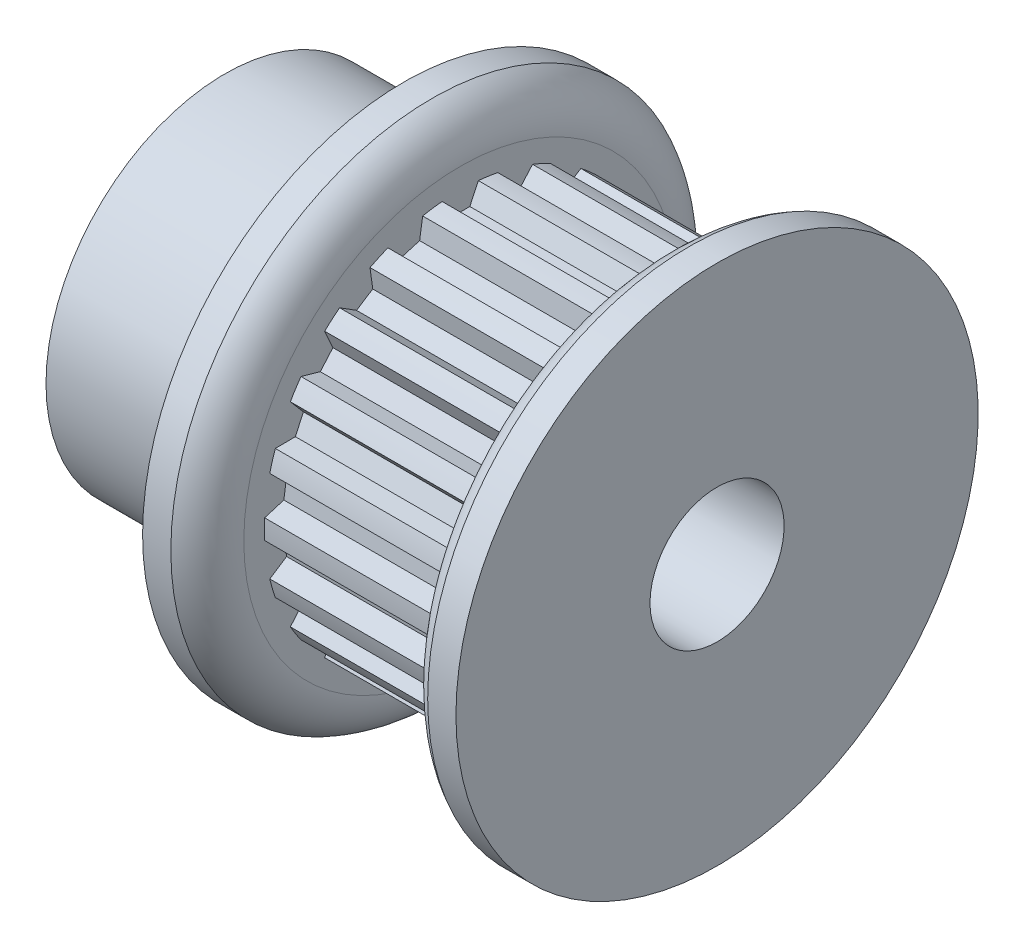
SolidWorks part; units mm, degrees
ref_plane "Front Plane" through (0, 0, 0) normal (0, 0, 1) x (1, 0, 0)
ref_plane "Top Plane" through (0, 0, 0) normal (0, 1, 0) x (1, 0, 0)
ref_plane "Right Plane" through (0, 0, 0) normal (1, 0, 0) x (0, 0, -1)
sketch "Sketch2" plane through (0, 0, 0) normal (1, 0, 0) x (0, 0, -1)
  line L3 (0, 0) -> (0, 6.2865) construction
  line L6 (0, -6.7945) -> (0, -7.112) construction
  line L7 (-0.5715, 6.7704) -> (-0.3415, 6.2772)
  line L8 (0.5715, 6.7704) -> (0.3415, 6.2772)
  line L9 (-0.5715, 6.7704) -> (-0.6429, 6.9235)
  line L10 (0.5715, 6.7704) -> (0.6429, 6.9235)
  line L12 (-0.3415, 6.2772) -> (0.3415, 6.2772)
  line L14 (0, 6.7945) -> (0, 7.112) construction
  line L15 (0, 0) -> (0, -1.143) construction
  circle A0 centre (0, 0) radius 7.112 construction
  circle A1 centre (0, 0) radius 6.2865 construction
  circle A2 centre (0, 0) radius 6.7945 construction
  arc A7 (0.6429, 6.9235) -> (-0.6429, 6.9235) centre (0, 0) ccw
  point P5 (0, 6.9533)
  dimension "D3" = 0.3175
  dimension "D1" = 50
sketch "Sketch1" plane through (0, 0, 0) normal (0, 0, 1) x (1, 0, 0)
  line L0 (-8.7376, 0) -> (8.7376, 0) construction
  line L1 (-8.7376, 2.3813) -> (8.7376, 2.3813)
  line L2 (-8.7376, 2.3813) -> (-8.7376, 6.35)
  line L3 (-2.3876, 9.271) -> (-1.3843, 9.271)
  line L4 (-0.381, 7.112) -> (-0.381, 7.6835)
  line L5 (-0.381, 8.255) -> (-0.381, 7.112) construction
  line L6 (-0.381, 7.112) -> (6.731, 7.112)
  line L7 (6.731, 7.112) -> (6.731, 7.6835)
  line L8 (6.731, 7.112) -> (8.7376, 7.112) construction
  line L9 (7.7343, 9.271) -> (8.7376, 9.271)
  line L10 (8.7376, 9.271) -> (8.7376, 2.3813)
  line L11 (7.7343, 7.112) -> (7.7343, 9.271) construction
  line L12 (-5.5626, 6.35) -> (-5.5626, 2.3812) construction
  line L13 (-2.3876, 9.271) -> (-2.3876, 6.35)
  line L14 (-2.3876, 6.35) -> (-8.7376, 6.35)
  arc A0 (6.731, 7.6835) -> (7.7343, 9.271) centre (8.4886, 7.6835) cw
  arc A1 (-0.381, 7.6835) -> (-1.3843, 9.271) centre (-2.1386, 7.6835) ccw
  dimension "Bore Size" = 4.7625
  dimension "Overall Width" = 17.4752
  dimension "Inside Width" = 7.112
  dimension "OD" = 18.542
  dimension "D2" = 14.224
  dimension "D3" = 1.143
  dimension "D4" = 0.5715
  dimension "Outside Width" = 11.1252
revolve "Revolve1" add sketch "Sketch1" angle 360 mid plane about L0
sketch "Sketch4" plane through (-0.381, 0, 0) normal (1, 0, 0) x (0, 0, -1)
  circle A0 centre (0, 0) radius 6.9533
  circle A2 centre (0, 0) radius 7.112
  circle A3 centre (0, 0) radius 7.112 construction
extrude "Cut-Extrude2" cut sketch "Sketch4" along normal up to surface (7.112 mm away) up to face at (6.731, 0, 7.112)
sketch "Sketch3" plane through (-0.381, 0, 0) normal (1, 0, 0) x (0, 0, -1)
  line L2 (-0.5715, 6.7704) -> (-0.3415, 6.2772) construction
  line L3 (-0.3415, 6.2772) -> (0.3415, 6.2772) construction
  line L4 (0.5715, 6.7704) -> (0.3415, 6.2772) construction
  line L5 (-0.6429, 6.9235) -> (-0.3415, 6.2772)
  line L6 (-0.3415, 6.2772) -> (0.3415, 6.2772)
  line L7 (0.6429, 6.9235) -> (0.3415, 6.2772)
  arc A1 (0.6429, 6.9235) -> (-0.6429, 6.9235) centre (0, 0) ccw construction
  arc A2 (0.6429, 6.9235) -> (-0.6429, 6.9235) centre (0, 0) ccw
extrude "Cut-Extrude1" cut sketch "Sketch3" along normal up to surface (7.112 mm away) up to face at (6.731, 0, 7.6835)
pattern_circular "CirPattern1" count 22 over 360 about axis through (0, 0, 0) along (1, 0, 0) of "Cut-Extrude1"
sketch "Sketch5" plane through (0, 0, 0) normal (0, 0, 1) x (1, 0, 0)
  line L1 (6.731, 7.6835) -> (6.731, -7.6835) construction
  point P0 (6.731, 0)
equation "\"D3@Sketch2\" = (\"hs@Sketch2\"-\"ht@Sketch2\")/2"
equation "\"D2@Sketch1\" = \"PD@Sketch2\""
equation "\"D3@Sketch1\" = \"hs@Sketch2\""
equation "\"D4@Sketch1\" = \"D3@Sketch1\"/2"
